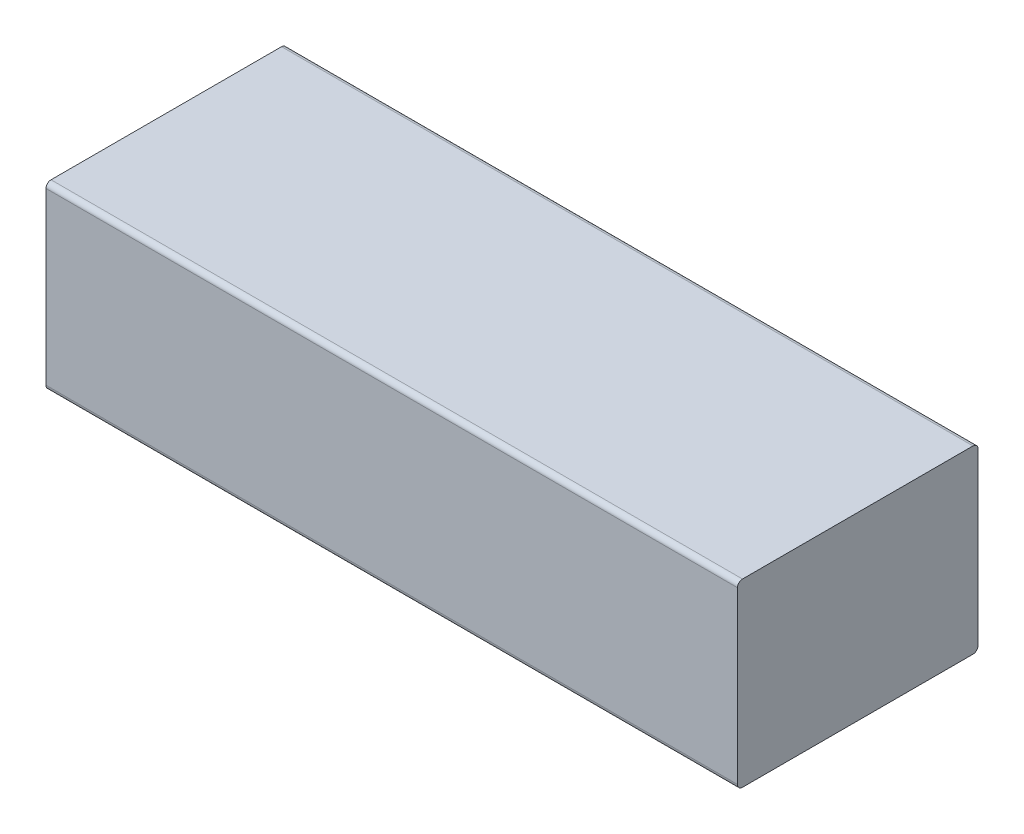
SolidWorks part; units mm, degrees
material "PLA"
ref_plane "Front Plane" through (0, 0, 0) normal (0, 0, 1) x (1, 0, 0)
ref_plane "Top Plane" through (0, 0, 0) normal (0, 1, 0) x (1, 0, 0)
ref_plane "Right Plane" through (0, 0, 0) normal (1, 0, 0) x (0, 0, -1)
sketch "Sketch1" plane through (0, 0, 0) normal (0, 0, 1) x (1, 0, 0)
  line L1 (0, 0) -> (138, 0)
  line L2 (0, 0) -> (0, 36)
  line L3 (0, 36) -> (138, 36)
  line L4 (138, 0) -> (138, 36)
  dimension "D1" = 138
  dimension "D2" = 36
extrude "Boss-Extrude1" add sketch "Sketch1" against normal blind 48
fillet "Fillet2" radius 1 4 edges at (69, 0, -48) (69, 0, 0) (69, 36, -48) (69, 36, 0)
sketch "Sketch2" plane through (0, 0, 0) normal (0, -1, 0) x (1, 0, 0)
  line L0 (0, -47) -> (0, -1) construction
  line L1 (0, -3.3736) -> (5.1211, -3.3736)
  line L2 (0, -3.3736) -> (0, -13.1008)
  line L3 (0, -13.1008) -> (5.1211, -13.1008)
  line L4 (5.1211, -3.3736) -> (5.1211, -13.1008)
extrude "Cut-Extrude1" cut sketch "Sketch2" against normal blind 4
